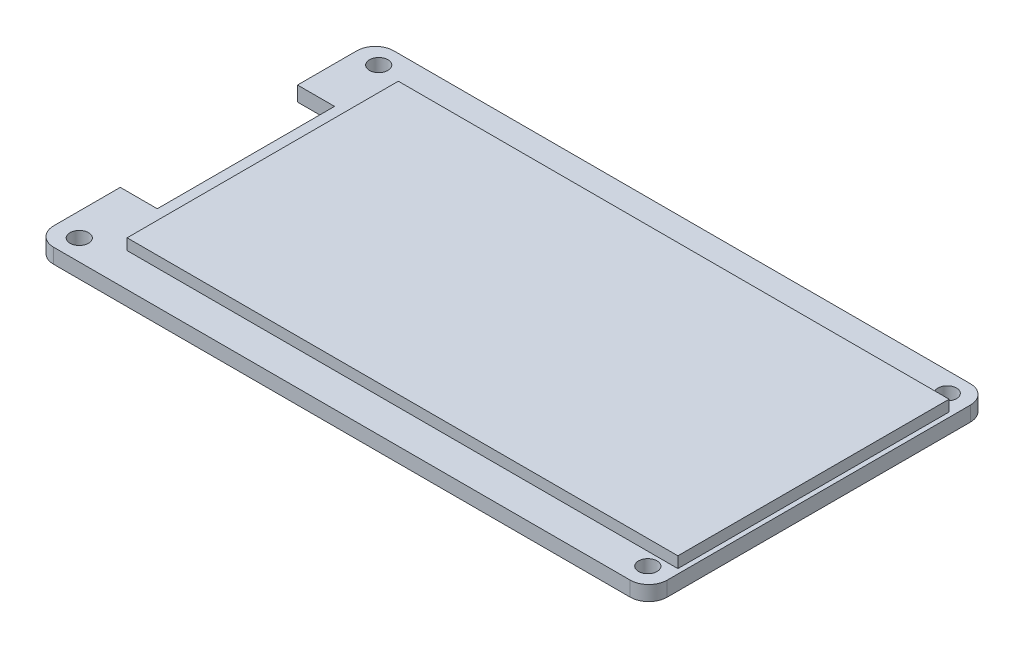
SolidWorks part; units mm, degrees
ref_plane "Front Plane" through (0, 0, 0) normal (0, 0, 1) x (1, 0, 0)
ref_plane "Top Plane" through (0, 0, 0) normal (0, 1, 0) x (1, 0, 0)
ref_plane "Right Plane" through (0, 0, 0) normal (1, 0, 0) x (0, 0, -1)
sketch "Sketch1" plane through (0, 0, 0) normal (0, 1, 0) x (1, 0, 0)
  line L0 (-33.145, -9.175) -> (-33.145, -16.375)
  line L1 (-31.145, 18.375) -> (31.145, 18.375)
  line L2 (-33.145, 16.375) -> (-33.145, 9.975)
  line L3 (-31.145, -18.375) -> (31.145, -18.375)
  line L4 (33.145, 16.375) -> (33.145, -16.375)
  line L5 (-33.145, 18.375) -> (33.145, -18.375) construction
  line L6 (-33.145, -18.375) -> (33.145, 18.375) construction
  line L7 (-33.145, 9.975) -> (-29.145, 9.975)
  line L9 (-33.145, -9.175) -> (-29.145, -9.175)
  line L10 (-29.145, 9.975) -> (-29.145, -9.175)
  circle A0 centre (-30.625, -16.125) radius 1
  circle A1 centre (30.795, -16.125) radius 1
  circle A2 centre (30.795, 16.225) radius 1
  circle A3 centre (-30.625, 16.225) radius 1
  arc A4 (-31.145, 18.375) -> (-33.145, 16.375) centre (-31.145, 16.375) ccw
  arc A5 (-33.145, -16.375) -> (-31.145, -18.375) centre (-31.145, -16.375) ccw
  arc A6 (33.145, -16.375) -> (31.145, -18.375) centre (31.145, -16.375) cw
  arc A7 (33.145, 16.375) -> (31.145, 18.375) centre (31.145, 16.375) ccw
  point P0 (0, 0)
  point P18 (0, 0)
  point P19 (0, 0)
  dimension "D6" = 2
  dimension "D11" = 2
  dimension "D1" = 36.75
  dimension "D2" = 66.29
  dimension "D3" = 8.4
  dimension "D4" = 9.2
  dimension "D5" = 4
  dimension "D7" = 2.25
  dimension "D8" = 2.52
  dimension "D9" = 2.15
  dimension "D10" = 2.35
extrude "Boss-Extrude1" add sketch "Sketch1" along normal blind 1.6
sketch "Sketch2" plane through (0, 1.6, 0) normal (0, 1, 0) x (1, 0, 0)
  line L0 (33.145, -16.375) -> (33.145, 16.375) construction
  line L1 (-26.855, 14.575) -> (32.645, 14.575)
  line L2 (-26.855, 14.575) -> (-26.855, -14.725)
  line L3 (-26.855, -14.725) -> (32.645, -14.725)
  line L4 (32.645, 14.575) -> (32.645, -14.725)
  line L5 (31.145, 18.375) -> (-31.145, 18.375) construction
  dimension "D1" = 0.5
  dimension "D2" = 3.8
  dimension "D3" = 29.3
  dimension "D4" = 59.5
extrude "Boss-Extrude2" add sketch "Sketch2" along normal blind 1.2
